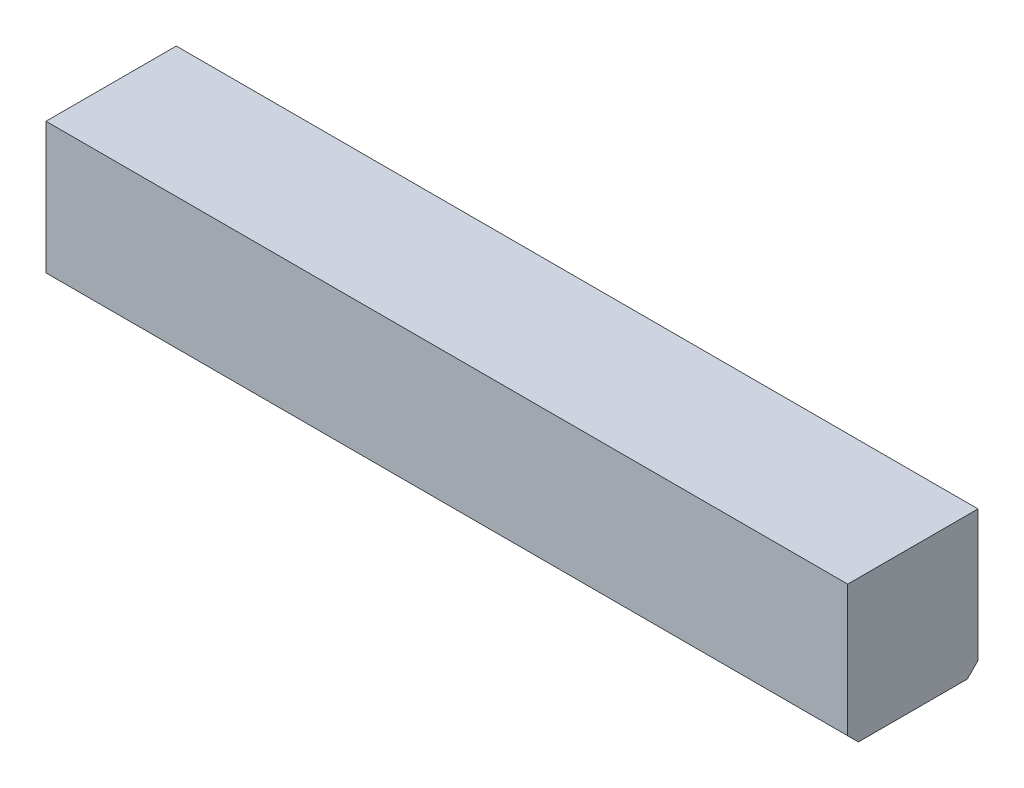
SolidWorks part; units mm, degrees
ref_plane "Front Plane" through (0, 0, 0) normal (0, 0, 1) x (1, 0, 0)
ref_plane "Top Plane" through (0, 0, 0) normal (0, 1, 0) x (1, 0, 0)
ref_plane "Right Plane" through (0, 0, 0) normal (1, 0, 0) x (0, 0, -1)
ref_plane "PX 30.000" through (30, 0, 0) normal (1, 0, 0) x (0, 0, -1)
sketch "spacer sketch" plane through (30, 0, 0) normal (1, 0, 0) x (0, 0, -1)
  line L0 (-0.8, 0) -> (0, 0.8)
  line L1 (0, 0.8) -> (0, 10.63)
  line L2 (0, 10.63) -> (-9.75, 10.63)
  line L3 (-9.75, 10.63) -> (-9.75, 0.8)
  line L4 (-9.75, 0.8) -> (-8.95, 0)
  line L5 (-8.95, 0) -> (-0.8, 0)
extrude "spacer" add sketch "spacer sketch" along normal mid plane 60
equation "\"diffL\" = 608.8mm"
equation "\"diffW\" = 329.4mm"
equation "\"diffT\" = 2.9mm"
equation "\"chanSlotW\" = 12.9mm"
equation "\"chanSlotDepth\" = 11.13mm"
equation "\"chanFloor\" = 1.57mm"
equation "\"chanLeg\" = 12.7mm"
equation "\"lightL\" = 604.8mm"
equation "\"lightW\" = 330.2mm"
equation "\"lightH\" = 92mm"
equation "\"lightSideFlat\" = 30mm"
equation "\"lightSlopeLen\" = 38.9mm"
equation "\"lightWingDepth\" = 50.1mm"
equation "\"lightWingFlat\" = 90.2mm"
equation "\"lightChanW\" = 99.6mm"
equation "\"lightChanStand\" = 44.1mm"
equation "\"insFlangeD\" = 12.3mm"
equation "\"insFromEnd\" = 20.7mm"
equation "\"insUpSlope\" = 20.8mm"
equation "\"gaugeH\" = 10mm"
equation "\"gaugeStepLen\" = 14mm"
equation "\"gaugeStepW0\" = 13.1mm"
equation "\"gaugeStepDW\" = 0.2mm"
equation "\"gaugeSteps\" = 5mm"
equation "\"gaugeHandleLen\" = 30mm"
equation "\"gaugeHandleW\" = 24mm"
equation "\"gaugeSlot0\" = 3mm"
equation "\"gaugeSlotD\" = 0.1mm"
equation "\"gaugeSlotDepth\" = 8mm"
equation "\"gap\" = 25.4mm"
equation "\"edgeL\" = 1mm"
equation "\"edgeW\" = 0.75mm"
equation "\"proud\" = 1.5mm"
equation "\"seatClr\" = 0.15mm"
equation "\"tongueClrZ\" = 0.1mm"
equation "\"tongueClrX\" = 0.25mm"
equation "\"tongueLen\" = 30mm"
equation "\"armSide\" = 45mm"
equation "\"armEnd\" = 20mm"
equation "\"cornerCham\" = 3mm"
equation "\"brkW\" = 26mm"
equation "\"brkT\" = 7mm"
equation "\"brkSeatClr\" = 0.3mm"
equation "\"brkScrewSpan\" = 16mm"
equation "\"pilotD\" = 2.7mm"
equation "\"pilotDepth\" = 10mm"
equation "\"screwClrD\" = 3.9mm"
equation "\"jogBelow\" = 4mm"
equation "\"padT\" = 7mm"
equation "\"padLen\" = 36mm"
equation "\"m6Clr\" = 7mm"
equation "\"m6Slot\" = 6mm"
equation "\"flangeRelD\" = 17mm"
equation "\"flangeRelDepth\" = 1.5mm"
equation "\"relLen\" = 5mm"
equation "\"relDepth\" = 3.3mm"
equation "\"knockN\" = 100mm"
equation "\"petgcfE\" = 3000mm"
equation "\"mockExtent\" = 110mm"
equation "\"relZnear\" = 9.4mm"
equation "\"relZfar\" = 23.4mm"
equation "\"headD\" = 8mm"
equation "\"headH\" = 2.5mm"
equation "\"headFromEnd\" = 6.8mm"
equation "\"headBack\" = 16.4mm"
equation "\"sideClr\" = 0.4mm"
equation "\"cornerRelR\" = 1.5mm"
equation "\"cornerRelBack\" = 0.6mm"
equation "\"endHeadH\" = 2.8mm"
equation "\"footClr\" = 1.2mm"
equation "\"footEndClr\" = 3.5mm"
equation "\"footLift\" = 6mm"
equation "\"footBlockClr\" = 0.5mm"
equation "\"footBack\" = 50mm"
equation "\"footFwd\" = 10mm"
equation "\"footRibH\" = 16mm"
equation "\"footRibT\" = 6mm"
equation "\"footBraceEnd\" = 3mm"
equation "\"footLoadN\" = 25mm"
equation "\"spacerLen\" = 60mm"
equation "\"spacerShort\" = 0.5mm"
equation "\"spacerCham\" = 0.8mm"
equation "\"spacerPerSide\" = 3mm"
equation "\"spacerPerEnd\" = 1mm"
